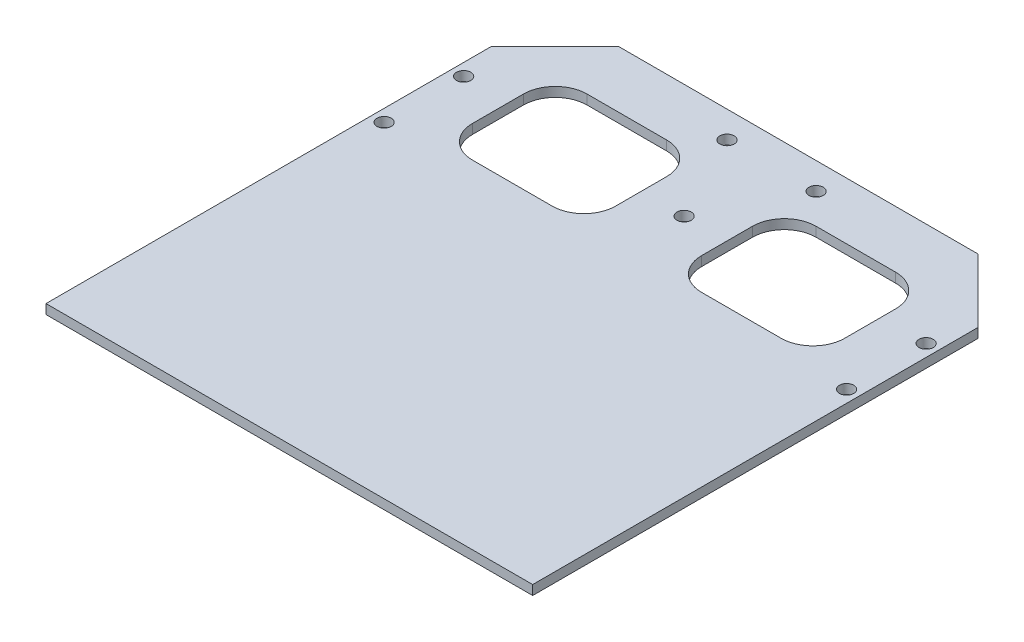
SolidWorks part; units mm, degrees
material "Thornel Mat VMA"
ref_plane "前视基准面" through (0, 0, 0) normal (0, 0, 1) x (1, 0, 0)
ref_plane "上视基准面" through (0, 0, 0) normal (0, 1, 0) x (1, 0, 0)
ref_plane "右视基准面" through (0, 0, 0) normal (1, 0, 0) x (0, 0, -1)
sketch "草图1" plane through (0, 0, 0) normal (0, 1, 0) x (1, 0, 0)
  line L1 (-76.5, 80) -> (76.5, 80)
  line L2 (-76.5, 80) -> (-76.5, -80)
  line L3 (-76.5, -80) -> (76.5, -80)
  line L4 (76.5, 80) -> (76.5, -80)
  line L5 (0, -80) -> (0, 80) construction
  line L6 (-76.5, 0) -> (76.5, 0) construction
  point P0 (0, 0)
  dimension "D1" = 153
  dimension "D2" = 160
extrude "凸台-拉伸1" add sketch "草图1" along normal blind 3
sketch "草图2" plane through (0, 3, 0) normal (0, 1, 0) x (1, 0, 0)
  line L0 (-76.5, 0) -> (76.5, 0) construction
  line L1 (-76.5, 80) -> (-76.5, -80) construction
  line L2 (76.5, -80) -> (76.5, 80) construction
  line L3 (0, 80) -> (0, -80) construction
  line L4 (76.5, 80) -> (-76.5, 80) construction
  line L5 (-76.5, -80) -> (76.5, -80) construction
  line L6 (-72.7, 47.5) -> (-72.7, 22.5) construction
  line L7 (-72.7, 22.5) -> (72.7, 22.5) construction
  line L8 (72.7, 22.5) -> (72.7, 47.5) construction
  line L9 (72.7, 47.5) -> (-72.7, 47.5) construction
  line L10 (-72.7, 35) -> (72.7, 35) construction
  circle A0 centre (72.7, 47.5) radius 2.25
  circle A1 centre (-72.7, 47.5) radius 2.25
  circle A2 centre (72.7, 22.5) radius 2.25
  circle A3 centre (-72.7, 22.5) radius 2.25
  circle A4 centre (-14, 71.6) radius 2.25
  circle A5 centre (14, 71.6) radius 2.25
  circle A6 centre (0, 44.1) radius 2.25
  dimension "D1" = 145.4
  dimension "D2" = 4.5
  dimension "D3" = 4.5
  dimension "D4" = 25
  dimension "D5" = 4.5
  dimension "D6" = 36.6
  dimension "D7" = 28
  dimension "D8" = 4.5
  dimension "D9" = 9.1
  dimension "D10" = 45
extrude "切除-拉伸1" cut sketch "草图2" against normal blind 5
sketch "草图3" plane through (0, 3, 0) normal (0, 1, 0) x (1, 0, 0)
  line L0 (0, 44.1) -> (65.3728, 44.1) construction
  line L1 (0, 80) -> (0, -80) construction
  line L2 (13.5, 62.1) -> (58.5, 62.1)
  line L3 (13.5, 62.1) -> (13.5, 26.1)
  line L4 (13.5, 26.1) -> (58.5, 26.1)
  line L5 (58.5, 62.1) -> (58.5, 26.1)
  line L6 (36, 26.1) -> (36, 62.1) construction
  line L7 (13.5, 44.1) -> (58.5, 44.1) construction
  line L8 (-13.5, 44.1) -> (-58.5, 44.1) construction
  line L9 (-36, 26.1) -> (-36, 62.1) construction
  line L10 (-58.5, 62.1) -> (-58.5, 26.1)
  line L11 (-13.5, 26.1) -> (-58.5, 26.1)
  line L12 (-13.5, 62.1) -> (-13.5, 26.1)
  line L13 (-13.5, 62.1) -> (-58.5, 62.1)
  point P3 (36, 44.1)
  point P17 (-36, 44.1)
  dimension "D1" = 36
  dimension "D2" = 45
  dimension "D3" = 36
extrude "切除-拉伸2" cut sketch "草图3" against normal blind 5
fillet "圆角1" radius 10 8 edges at (58.5, 1.5, -26.1) (13.5, 1.5, -26.1) (13.5, 1.5, -62.1) (58.5, 1.5, -62.1) (-13.5, 1.5, -26.1) (-58.5, 1.5, -26.1) (-58.5, 1.5, -62.1) (-13.5, 1.5, -62.1)
chamfer "倒角1" distance 20 angle 45 2 edges at (76.5, 1.5, -80) (-76.5, 1.5, -80)
